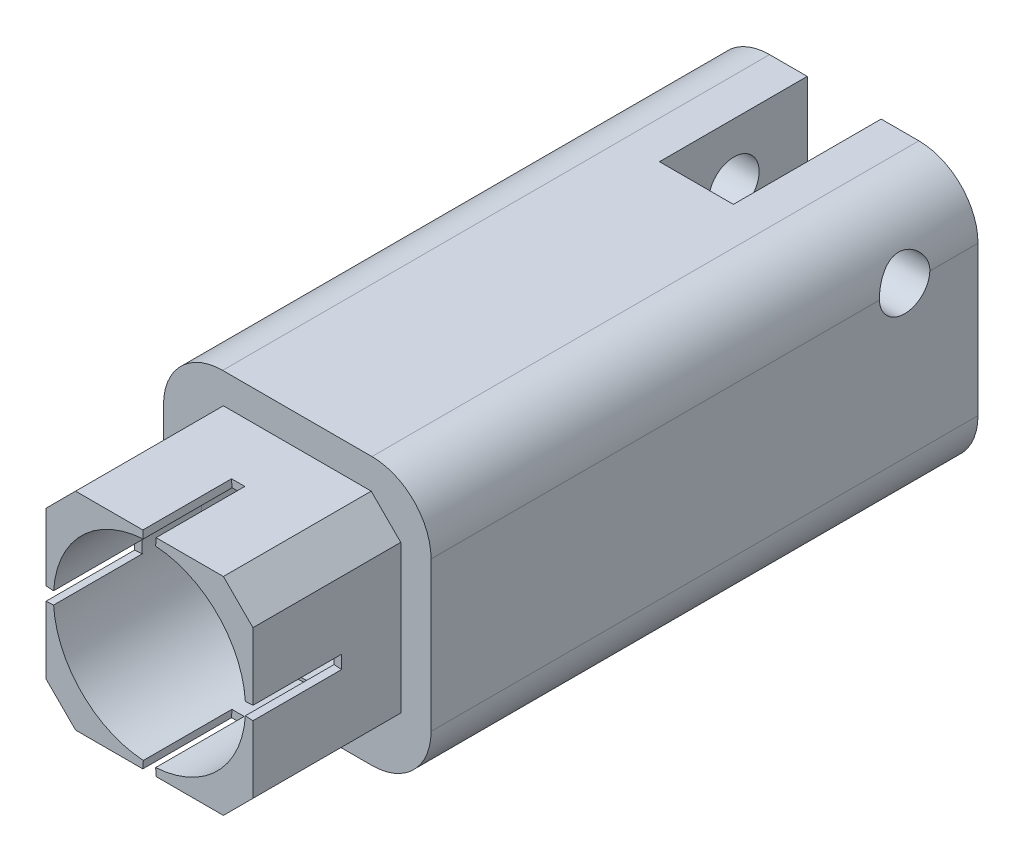
SolidWorks part; units mm, degrees
ref_plane "Front Plane" through (0, 0, 0) normal (0, 0, 1) x (1, 0, 0)
ref_plane "Top Plane" through (0, 0, 0) normal (0, 1, 0) x (1, 0, 0)
ref_plane "Right Plane" through (0, 0, 0) normal (1, 0, 0) x (0, 0, -1)
sketch "Sketch1" plane through (0, 0, 0) normal (0, 0, 1) x (1, 0, 0)
  line L0 (-5.05, 9.05) -> (5.05, 9.05)
  line L1 (9.05, -5.05) -> (9.05, 5.05)
  line L2 (0, 0) -> (0, 14.1446) construction
  line L3 (-9.05, -5.05) -> (-9.05, 5.05)
  line L4 (-12.732, 0) -> (15.0845, 0) construction
  line L5 (-5.05, -9.05) -> (5.05, -9.05)
  arc A4 (5.05, 9.05) -> (9.05, 5.05) centre (5.05, 5.05) cw
  arc A5 (9.05, -5.05) -> (5.05, -9.05) centre (5.05, -5.05) cw
  arc A6 (-5.05, -9.05) -> (-9.05, -5.05) centre (-5.05, -5.05) cw
  arc A7 (-9.05, 5.05) -> (-5.05, 9.05) centre (-5.05, 5.05) cw
  point P11 (9.05, 0)
  point P12 (0, 9.05)
  point P20 (0, -9.05)
  point P21 (-9.05, 0)
  dimension "D3" = 0
  dimension "D1" = 5.05
  dimension "D2" = 5.05
  dimension "D4" = 9.05
  dimension "D5" = 9.05
extrude "Boss-Extrude1" add sketch "Sketch1" along normal blind 37
sketch "Sketch3" plane through (0, 0, 37) normal (0, 0, 1) x (1, 0, 0)
  line L0 (-5, -7) -> (5, -7)
  line L1 (-7, -5) -> (-7, 5)
  line L2 (-5, 7) -> (5, 7)
  line L3 (7, -5) -> (7, 5)
  line L4 (-7, -7) -> (7, 7) construction
  line L5 (-7, 7) -> (7, -7) construction
  line L6 (-5, 7) -> (-7, 5)
  line L7 (5, 7) -> (7, 5)
  line L8 (7, -5) -> (5, -7)
  line L9 (-5, -7) -> (-7, -5)
  circle A6 centre (0, 0) radius 6.5
  point P3 (0, 0)
  dimension "D1" = 14
  dimension "D3" = 13
  dimension "D4" = 0
  dimension "D5" = 0
  dimension "D6" = 0
extrude "Boss-Extrude2" add sketch "Sketch3" along normal blind 10
sketch "Sketch11" plane through (0, 0, 47) normal (0, 0, 1) x (1, 0, 0)
  line L0 (0, 0) -> (7, 0.45)
  line L1 (7, -5) -> (7, 5) construction
  line L2 (7, 0.45) -> (7, -0.45)
  line L3 (7, -0.45) -> (0, 0)
  dimension "D1" = 0.45
  dimension "D2" = 0.45
extrude "Cut-Extrude7" cut sketch "Sketch11" against normal blind 6
pattern_circular "CirPattern1" count 4 over 360 about axis through (0, 0, 47) along (0, 0, -1) of "Cut-Extrude7"
sketch "Sketch12" plane through (0, 0, 37) normal (0, 0, 1) x (1, 0, 0)
  line L0 (0, 0) -> (0, 14.1446) construction
  circle A0 centre (0, 0.1925) radius 6.5
  dimension "D1" = 13
extrude "Cut-Extrude8" cut sketch "Sketch12" against normal blind 25
sketch "Sketch13" plane through (0, 0, 0) normal (0, 0, 1) x (1, 0, 0)
  line L0 (-12.732, 0) -> (15.0845, 0) construction
  line L3 (-2.5, 0) -> (-2.5, 9.05)
  line L4 (-5.05, 9.05) -> (5.05, 9.05) construction
  line L5 (-2.5, 9.05) -> (2.5, 9.05)
  line L6 (2.5, 9.05) -> (2.5, 0)
  arc A0 (-2.5, 0) -> (2.5, 0) centre (0, 0) ccw
  dimension "D2" = 2.5
  dimension "D1" = 0
extrude "Cut-Extrude9" cut sketch "Sketch13" along normal blind 10
sketch "Sketch14" plane through (0, 0, 0) normal (1, 0, 0) x (0, 0, -1)
  circle A0 centre (-4.9636, 5.105) radius 1.705
  dimension "D1" = 3.41
  dimension "D2" = 5.105
extrude "Cut-Extrude10" cut sketch "Sketch14" against normal mid plane 25
